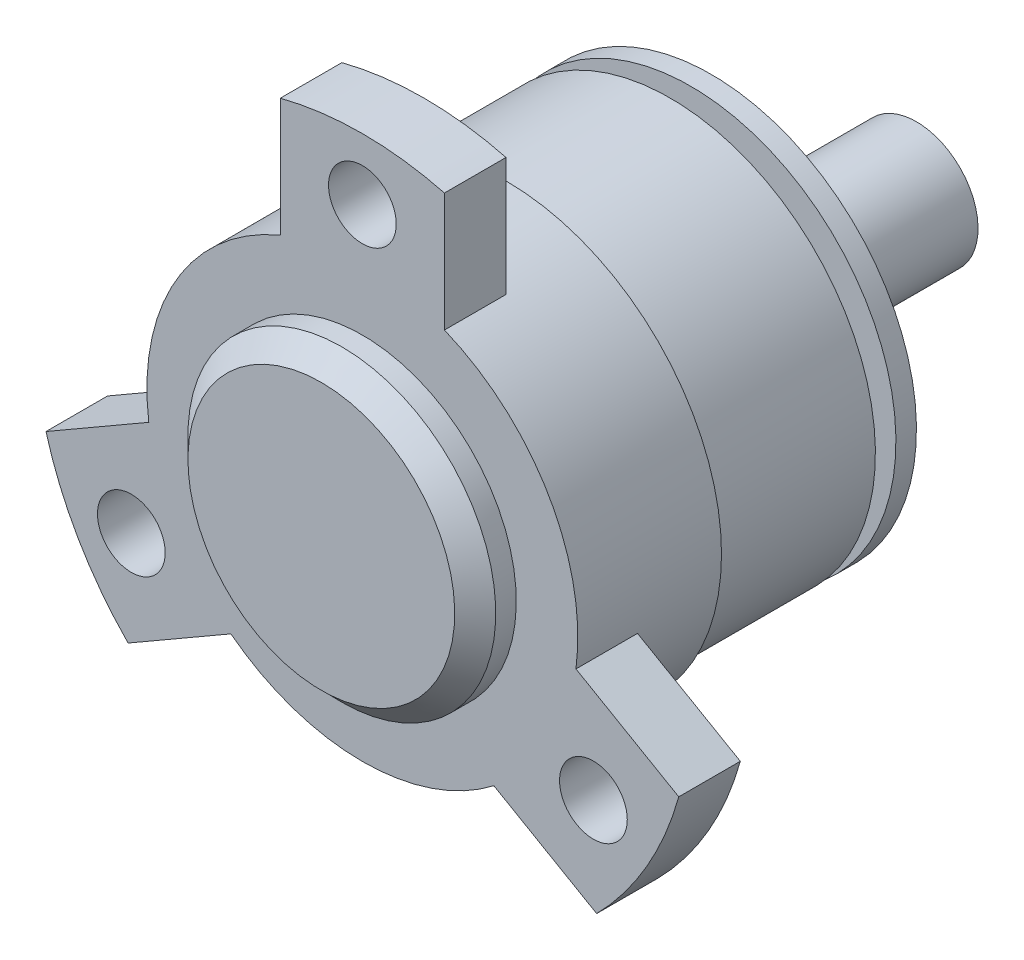
SolidWorks part; units mm, degrees
material "1060 合金"
ref_plane "前视基准面" through (0, 0, 0) normal (0, 0, 1) x (1, 0, 0)
ref_plane "上视基准面" through (0, 0, 0) normal (0, 1, 0) x (1, 0, 0)
ref_plane "右视基准面" through (0, 0, 0) normal (1, 0, 0) x (0, 0, -1)
sketch "草图1" plane through (0, 0, 0) normal (1, 0, 0) x (0, 0, -1)
  line L0 (0, 43.0226) -> (0, 0) construction
  line L1 (0, 0) -> (29, 0)
  line L2 (18, 10) -> (19, 10)
  line L4 (0, 0) -> (0, 7.5)
  line L5 (0, 7.5) -> (2, 7.5)
  line L7 (29, 0) -> (63.4157, 0) construction
  line L8 (2, 7.5) -> (2, 16)
  line L9 (2, 16) -> (5, 16)
  line L10 (5, 10.5) -> (5, 16)
  line L11 (5, 10.5) -> (9, 10.5)
  line L12 (19, 3) -> (29, 3)
  line L14 (9, 10.5) -> (9, 10)
  line L16 (29, 3) -> (29, 0)
  line L17 (9, 10) -> (17, 10)
  line L18 (19, 3) -> (19, 10)
  line L20 (17, 10) -> (17, 8.5)
  line L21 (17, 8.5) -> (18, 8.5)
  line L22 (18, 10) -> (18, 8.5)
  dimension "D1" = 2
  dimension "D2" = 7.5
  dimension "D3" = 16
  dimension "D4" = 3
  dimension "D5" = 4
  dimension "D6" = 10
  dimension "D7" = 3
  dimension "D8" = 1
  dimension "D9" = 1.5
  dimension "D10" = 1
  dimension "D11" = 0.5
  dimension "D12" = 10
  dimension "D13" = 10
revolve "旋转1" add sketch "草图1" angle 360 about L1
hole_wizard "M4 螺纹孔1" positions "草图3" profile "草图2" tap size "M4" standard "GB" end condition through all
sketch "草图3" plane through (0, 0, -2) normal (0, 0, 1) x (1, 0, 0)
  line L0 (0, 0) -> (0, 19.3219) construction
  circle A0 centre (0, 0) radius 13 construction
  point P0 (0, 13)
  point P23 (11.2583, -6.5)
  point P24 (-11.2583, -6.5)
  point P25 (0, 13) [skipped]
  dimension "D1" = 26
  dimension "D2" = 3
sketch "草图2" plane through (0, 13, -2) normal (1, 0, 0) x (0, -1, 0)
  line L0 (0, 0) -> (0, 27)
  line L1 (0, 27) -> (1.65, 27)
  line L2 (1.65, 27) -> (1.65, 0)
  line L5 (1.65, 0) -> (0, 0)
  line L11 (0, -6.35) -> (0, 107.95) construction
  dimension "通孔螺纹孔钻头直径" = 3.3
  dimension "通孔螺纹孔钻头深度" = 27
cosmetic thread "孔螺蚊线1" parameters "D2"=4
cosmetic thread "孔螺蚊线2" parameters "D2"=4
cosmetic thread "孔螺蚊线3" parameters "D2"=4
sketch "草图4" plane through (0, 0, -2) normal (0, 0, 1) x (1, 0, 0)
  line L0 (0, 0) -> (0, 18.9172) construction
  line L1 (4, 15.4919) -> (4, 9.7082)
  line L2 (-4, 15.4919) -> (-4, 9.7082)
  line L3 (15.4164, -4.2819) -> (10.4076, -1.39)
  line L4 (11.4164, -11.2101) -> (6.4076, -8.3182)
  line L5 (-11.4164, -11.2101) -> (-6.4076, -8.3182)
  line L6 (-15.4164, -4.2819) -> (-10.4076, -1.39)
  circle A0 centre (0, 0) radius 16 construction
  arc A1 (4, 15.4919) -> (-4, 15.4919) centre (0, 0) ccw
  arc A2 (-4, 9.7082) -> (-10.4076, -1.39) centre (0, 0) ccw
  arc A4 (11.4164, -11.2101) -> (15.4164, -4.2819) centre (0, 0) ccw
  arc A5 (10.4076, -1.39) -> (4, 9.7082) centre (0, 0) ccw
  arc A6 (-15.4164, -4.2819) -> (-11.4164, -11.2101) centre (0, 0) ccw
  arc A7 (-6.4076, -8.3182) -> (6.4076, -8.3182) centre (0, 0) ccw
  circle A9 centre (0, 0) radius 10.5 construction
  arc A10 (4, 10.247) -> (-4, 10.247) centre (0, 0) ccw [skipped]
  arc A11 (-10.8741, -1.6594) -> (-6.8741, -8.5876) centre (0, 0) ccw [skipped]
  arc A12 (6.8741, -8.5876) -> (10.8741, -1.6594) centre (0, 0) ccw [skipped]
  dimension "D2" = 8
  dimension "D3" = 3
extrude "切除-拉伸4" cut sketch "草图4" against normal up to surface (3 mm away) flip side to cut up to face at (0, 11.35, -5)
chamfer "倒角1" distance 1 angle 45 1 edges at (0, -7.5, 0)
